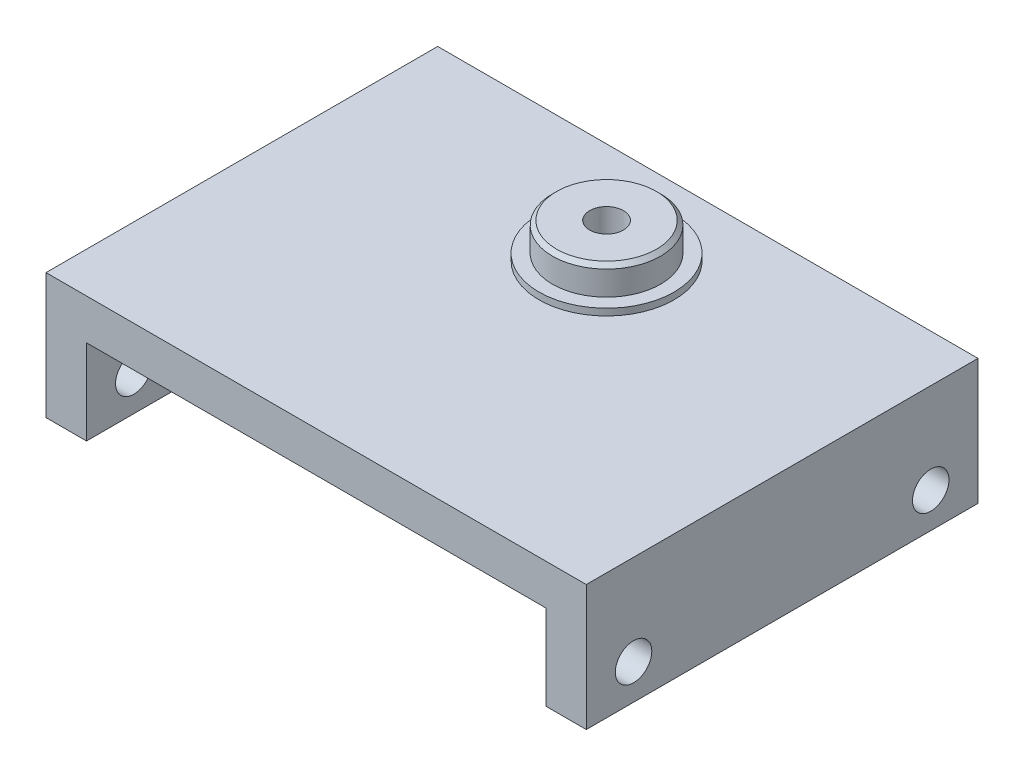
SolidWorks part; units mm, degrees
ref_plane "前视基准面" through (0, 0, 0) normal (0, 0, 1) x (1, 0, 0)
ref_plane "上视基准面" through (0, 0, 0) normal (0, 1, 0) x (1, 0, 0)
ref_plane "右视基准面" through (0, 0, 0) normal (1, 0, 0) x (0, 0, -1)
sketch "草图1" plane through (0, 0, 0) normal (0, 0, 1) x (1, 0, 0)
  line L0 (20, 0) -> (-20, 0)
  line L1 (-20, 0) -> (-20, -9.3)
  line L2 (-20, -9.3) -> (-17, -9.3)
  line L3 (-17, -9.3) -> (-17, -3)
  line L4 (-17, -3) -> (17, -3)
  line L5 (0, -3) -> (0, 14.0003) construction
  line L6 (17, -9.3) -> (17, -3)
  line L7 (20, -9.3) -> (17, -9.3)
  line L8 (20, 0) -> (20, -9.3)
  point P12 (0, 0)
  dimension "D1" = 40
  dimension "D2" = 9.3
  dimension "D3" = 3
  dimension "D4" = 3
extrude "凸台-拉伸1" add sketch "草图1" along normal blind 29
hole_wizard "Ø2.7 (2.7) 直径孔1" positions "草图3" profile "草图2" hole size "Ø2.7" standard "GB" end condition through all
sketch "草图3" plane through (20, 0, 0) normal (1, 0, 0) x (0, 0, -1)
  line L0 (-29, -9.3) -> (0, -9.3) construction
  line L1 (-14.5, -9.3) -> (-14.5, -3.21) construction
  point P0 (-25.5, -6.7)
  point P2 (-3.5, -6.7)
  dimension "D1" = 22
  dimension "D2" = 2.6
sketch "草图2" plane through (20, -6.7, 25.5) normal (0, 1, 0) x (0, 0, -1)
  line L0 (0, 0) -> (0, 40)
  line L1 (0, 40) -> (1.35, 40)
  line L2 (1.35, 40) -> (1.35, 0)
  line L5 (1.35, 0) -> (0, 0)
  line L11 (0, -6.35) -> (0, 107.95) construction
  dimension "通孔孔直径" = 2.7
  dimension "通孔孔深度" = 40
sketch "草图4" plane through (0, 0, 0) normal (0, 1, 0) x (1, 0, 0)
  line L0 (0, -7.5) -> (0, 0) construction
  circle A0 centre (0, -7.5) radius 4
  dimension "D1" = 8
  dimension "D2" = 7.5
extrude "凸台-拉伸2" add sketch "草图4" along normal blind 2.6
sketch "草图5" plane through (0, 0, 0) normal (0, 1, 0) x (1, 0, 0)
  circle A0 centre (0, -7.5) radius 5
  dimension "D1" = 10
extrude "凸台-拉伸3" add sketch "草图5" along normal blind 0.5
hole_wizard "M3 螺纹孔的螺纹孔钻头1" positions "草图7" profile "草图6" hole size "M3" standard "GB" end condition through all
sketch "草图7" plane through (0, 2.6, 0) normal (0, 1, 0) x (1, 0, 0)
  point P0 (0, -7.5)
sketch "草图6" plane through (0, 2.6, 7.5) normal (1, 0, 0) x (0, 0, 1)
  line L0 (0, 0) -> (0, 11.9)
  line L1 (0, 11.9) -> (1.25, 11.9)
  line L2 (1.25, 11.9) -> (1.25, 0)
  line L5 (1.25, 0) -> (0, 0)
  line L11 (0, -6.35) -> (0, 107.95) construction
  dimension "通孔孔直径" = 2.5
  dimension "通孔孔深度" = 11.9
chamfer "倒角2" distance 0.3 angle 45 1 edges at (0, 2.6, 11.5)
